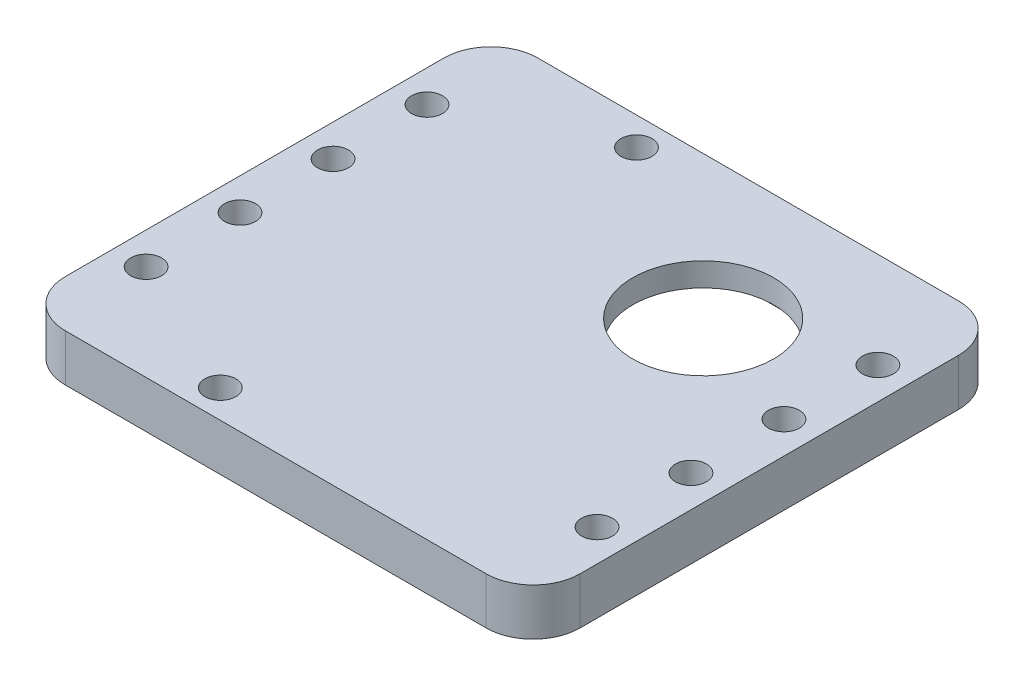
SolidWorks part; units mm, degrees
material "Alliage 1060"
ref_plane "Plan de face" through (0, 0, 0) normal (0, 0, 1) x (1, 0, 0)
ref_plane "Plan de dessus" through (0, 0, 0) normal (0, 1, 0) x (1, 0, 0)
ref_plane "Plan de droite" through (0, 0, 0) normal (1, 0, 0) x (0, 0, -1)
sketch "Esquisse1" plane through (0, 0, 0) normal (0, 1, 0) x (1, 0, 0)
  line L0 (-32.8, -35.1) -> (12, -35.1)
  line L1 (17, -30.1) -> (17, 10.2)
  line L2 (12, 15.2) -> (-32.8, 15.2)
  line L3 (-37.8, 10.2) -> (-37.8, -30.1)
  line L4 (10, 7.95) -> (10, -7.95) construction
  line L6 (-30.8, -7.95) -> (-30.8, 7.95) construction
  arc A0 (12, -35.1) -> (17, -30.1) centre (12, -30.1) ccw
  arc A1 (17, 10.2) -> (12, 15.2) centre (12, 10.2) ccw
  arc A2 (-32.8, 15.2) -> (-37.8, 10.2) centre (-32.8, 10.2) ccw
  arc A3 (-37.8, -30.1) -> (-32.8, -35.1) centre (-32.8, -30.1) ccw
  circle A4 centre (-19.3, -32.1) radius 3.5 construction
  circle A5 centre (-19.3, 12.2) radius 3.5 construction
  point P14 (-19.3, 12.2)
  point P15 (-19.3, -32.1)
  dimension "D3" = 5
  dimension "D4" = 7
  dimension "D1" = 3
  dimension "D2" = 3
  dimension "D6" = 7
extrude "Extrusion1" add sketch "Esquisse1" against normal blind 5
sketch "Esquisse6" plane through (0, -5, 0) normal (0, -1, 0) x (1, 0, 0)
  line L1 (1, 9.95) -> (-21.8, 9.95)
  line L2 (10, 0.95) -> (10, -0.95)
  line L3 (1, -9.95) -> (-21.8, -9.95)
  line L4 (-30.8, 0.95) -> (-30.8, -0.95)
  line L8 (10, 7.95) -> (10, -7.95) construction
  line L9 (8, -9.95) -> (-28.8, -9.95) construction
  line L10 (-28.8, 9.95) -> (8, 9.95) construction
  line L11 (-30.8, -7.95) -> (-30.8, 7.95) construction
  arc A0 (-30.8, -0.95) -> (-21.8, -9.95) centre (-21.8, -0.95) ccw
  arc A1 (1, -9.95) -> (10, -0.95) centre (1, -0.95) ccw
  arc A2 (10, 0.95) -> (1, 9.95) centre (1, 0.95) ccw
  arc A3 (-21.8, 9.95) -> (-30.8, 0.95) centre (-21.8, 0.95) ccw
  dimension "D1" = 9
extrude "Enlèv. mat.-Extru.2" cut sketch "Esquisse6" against normal blind 2.5
sketch "Esquisse10" plane through (0, -5, 0) normal (0, -1, 0) x (1, 0, 0)
  line L0 (-28.8, 9.95) -> (8, 9.95) construction
  line L1 (8, 9.95) -> (-28.8, 9.95)
  line L2 (10, 11.95) -> (10, 27.85)
  line L3 (8, 29.85) -> (-28.8, 29.85)
  line L4 (-30.8, 11.95) -> (-30.8, 27.85)
  line L5 (10, 11.95) -> (10, 27.85) construction
  line L6 (8, 29.85) -> (-28.8, 29.85) construction
  line L7 (-30.8, 27.85) -> (-30.8, 11.95) construction
  arc A0 (8, 9.95) -> (10, 11.95) centre (8, 11.95) ccw
  arc A1 (-28.8, 9.95) -> (-30.8, 11.95) centre (-28.8, 11.95) cw
  arc A2 (10, 27.85) -> (8, 29.85) centre (8, 27.85) ccw
  arc A3 (-28.8, 29.85) -> (-30.8, 27.85) centre (-28.8, 27.85) ccw
  dimension "D1" = 2
  dimension "D2" = 2
extrude "Enlèv. mat.-Extru.4" cut sketch "Esquisse10" against normal blind 1.8
sketch "Esquisse7" plane through (0, -2.5, 0) normal (0, -1, 0) x (1, 0, 0)
  circle A0 centre (0, 0) radius 7.5
  circle A1 centre (0, 0) radius 2.9 construction
  dimension "D1" = 15
extrude "Enlèv. mat.-Extru.3" cut sketch "Esquisse7" against normal through all
hole_wizard "Trou taraudé M4x0.71" positions "Esquisse9" profile "Esquisse8" tap size "M4x0.7" standard "Ansi Métrique" end condition through all
sketch "Esquisse9" plane through (0, -5, 0) normal (0, -1, 0) x (1, 0, 0)
  arc A4 (14.9151, -3.4932) -> (14.9151, -6.5068) centre (13.6, -5) ccw construction
  arc A5 (14.9151, 6.5068) -> (14.9151, 3.4932) centre (13.6, 5) ccw construction
  arc A6 (-35.7151, 3.4932) -> (-35.7151, 6.5068) centre (-34.4, 5) ccw construction
  arc A7 (-35.7151, -6.5068) -> (-35.7151, -3.4932) centre (-34.4, -5) ccw construction
  arc A8 (15.1123, 16.6329) -> (15.1123, 13.1671) centre (13.6, 14.9) ccw construction
  arc A9 (15.1123, 26.6329) -> (15.1123, 23.1671) centre (13.6, 24.9) ccw construction
  circle A10 centre (-19.3, 32.1) radius 3.5 construction
  arc A11 (-35.9123, 23.1671) -> (-35.9123, 26.6329) centre (-34.4, 24.9) ccw construction
  arc A12 (-35.9123, 13.1671) -> (-35.9123, 16.6329) centre (-34.4, 14.9) ccw construction
  circle A13 centre (-19.3, -12.2) radius 3.5 construction
  point P0 (-34.4, 5)
  point P1 (-34.4, -5)
  point P3 (13.6, 5)
  point P5 (13.6, -5)
  point P36 (-19.3, -12.2)
  point P38 (-19.3, 32.1)
  point P40 (13.6, 24.9)
  point P42 (13.6, 14.9)
  point P44 (-34.4, 14.9)
  point P46 (-34.4, 24.9)
sketch "Esquisse8" plane through (-34.4, -5, 5) normal (1, 0, 0) x (0, 0, -1)
  line L0 (0, 0) -> (0, 5)
  line L1 (0, 5) -> (1.65, 5)
  line L2 (1.65, 5) -> (1.65, 0)
  line L5 (1.65, 0) -> (0, 0)
  line L11 (0, -6.35) -> (0, 107.95) construction
  dimension "Diamètre du trou pour taraudage jusqu'au prochain" = 3.3
  dimension "Profondeur du trou pour taraudage jusqu'au prochain" = 5
cosmetic thread "Filetage de perçage1" parameters "D2"=4
cosmetic thread "Filetage de perçage2" parameters "D2"=4
cosmetic thread "Filetage de perçage3" parameters "D2"=4
cosmetic thread "Filetage de perçage4" parameters "D2"=4
cosmetic thread "Filetage de perçage5" parameters "D2"=4
cosmetic thread "Filetage de perçage6" parameters "D2"=4
cosmetic thread "Filetage de perçage7" parameters "D2"=4
cosmetic thread "Filetage de perçage8" parameters "D2"=4
cosmetic thread "Filetage de perçage9" parameters "D2"=4
cosmetic thread "Filetage de perçage10" parameters "D2"=4
